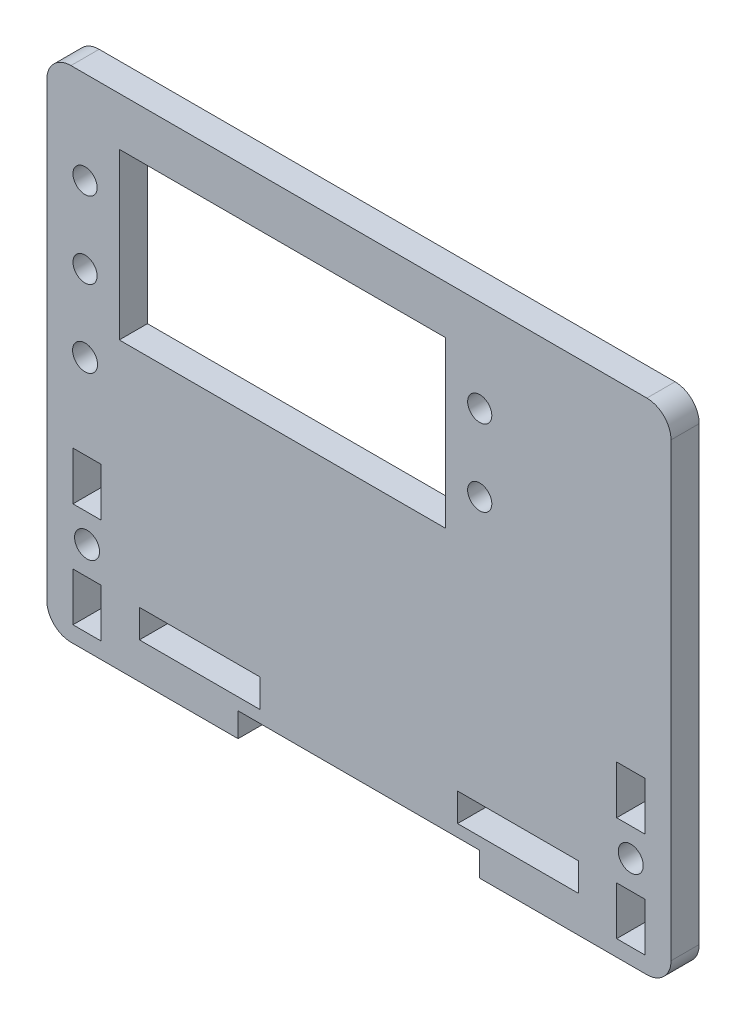
SolidWorks part; units mm, degrees
material "Balsa"
ref_plane "Front Plane" through (0, 0, 0) normal (0, 0, 1) x (1, 0, 0)
ref_plane "Top Plane" through (0, 0, 0) normal (0, 1, 0) x (1, 0, 0)
ref_plane "Right Plane" through (0, 0, 0) normal (1, 0, 0) x (0, 0, -1)
sketch "Sketch1" plane through (0, 0, 0) normal (0, 0, 1) x (1, 0, 0)
  line L1 (-35.75, -31) -> (35.75, -31)
  line L2 (-38.75, -28) -> (-38.75, 28)
  line L3 (-35.75, 31) -> (35.75, 31)
  line L4 (38.75, -28) -> (38.75, 28)
  line L5 (0, 31) -> (0, -31) construction
  line L6 (-38.75, 0) -> (38.75, 0) construction
  line L7 (-29.75, 4.5) -> (10.75, 4.5)
  line L8 (-29.75, 4.5) -> (-29.75, 25)
  line L9 (-29.75, 25) -> (10.75, 25)
  line L10 (10.75, 4.5) -> (10.75, 25)
  arc A0 (35.75, 31) -> (38.75, 28) centre (35.75, 28) cw
  arc A1 (35.75, -31) -> (38.75, -28) centre (35.75, -28) ccw
  arc A2 (-35.75, -31) -> (-38.75, -28) centre (-35.75, -28) cw
  arc A3 (-38.75, 28) -> (-35.75, 31) centre (-35.75, 28) cw
  point P0 (0, 0)
  point P8 (38.75, -31)
  point P12 (-38.75, -31)
  dimension "D2" = 3
  dimension "D3" = 62
  dimension "D1" = 28
  dimension "D4" = 40.5
  dimension "D5" = 20.5
  dimension "D6" = 9
  dimension "D7" = 6
extrude "Boss-Extrude1" add sketch "Sketch1" along normal blind 3.5
sketch "Sketch2" plane through (0, 0, 3.5) normal (0, 0, 1) x (1, 0, 0)
  line L0 (-38.75, -19.5) -> (38.75, -19.5) construction
  line L1 (-35.75, -31) -> (35.75, -31) construction
  line L2 (38.75, -28) -> (38.75, 28) construction
  line L3 (-38.75, 28) -> (-38.75, -28) construction
  line L4 (33.75, -29.922) -> (33.75, 0) construction
  line L5 (32, -16) -> (35.5, -16)
  line L6 (32, -16) -> (32, -10)
  line L7 (32, -10) -> (35.5, -10)
  line L8 (35.5, -16) -> (35.5, -10)
  line L9 (35.5, -23) -> (32, -23)
  line L10 (35.5, -23) -> (35.5, -29)
  line L11 (35.5, -29) -> (32, -29)
  line L12 (32, -23) -> (32, -29)
  line L13 (0, 10.4666) -> (0, -9.03) construction
  line L14 (-35.5, -23) -> (-32, -23)
  line L15 (-32, -23) -> (-32, -29)
  line L16 (-35.5, -29) -> (-32, -29)
  line L17 (-35.5, -23) -> (-35.5, -29)
  line L18 (-32, -16) -> (-35.5, -16)
  line L19 (-32, -16) -> (-32, -10)
  line L20 (-32, -10) -> (-35.5, -10)
  line L21 (-35.5, -16) -> (-35.5, -10)
  circle A1 centre (33.75, -19.5) radius 1.55
  circle A2 centre (-33.75, -19.5) radius 1.55
  dimension "D2" = 0
  dimension "D9" = 3.1
  dimension "D1" = 11.5
  dimension "D3" = 6
  dimension "D4" = 3.5
  dimension "D5" = 6
  dimension "D6" = 19
  dimension "D8" = 5
extrude "Cut-Extrude1" cut sketch "Sketch2" against normal through all
sketch "Sketch3" plane through (0, 0, 3.5) normal (0, 0, 1) x (1, 0, 0)
  line L0 (-32, -23) -> (32, -23) construction
  line L1 (0, 0) -> (0, -31) construction
  line L2 (-27.25, -23) -> (-12.25, -23)
  line L3 (-27.25, -23) -> (-27.25, -26.5)
  line L4 (-27.25, -26.5) -> (-12.25, -26.5)
  line L5 (-12.25, -23) -> (-12.25, -26.5)
  line L6 (-35.75, -31) -> (35.75, -31) construction
  line L8 (27.25, -23) -> (27.25, -26.5)
  line L9 (27.25, -23) -> (12.25, -23)
  line L10 (12.25, -23) -> (12.25, -26.5)
  line L11 (27.25, -26.5) -> (12.25, -26.5)
  dimension "D1" = 24.5
  dimension "D2" = 15
  dimension "D3" = 3.5
extrude "Cut-Extrude2" cut sketch "Sketch3" against normal through all
sketch "Sketch4" plane through (0, 0, 3.5) normal (0, 0, 1) x (1, 0, 0)
  line L0 (-32.7283, 14.75) -> (20.2148, 14.75) construction
  line L1 (10.75, 25) -> (-29.75, 25) construction
  line L2 (-9.5, -1.2649) -> (-9.5, 28.2785) construction
  line L3 (-29.75, 4.5) -> (10.75, 4.5) construction
  line L4 (-29.75, 25) -> (-29.75, 4.5) construction
  line L5 (10.75, 4.5) -> (10.75, 25) construction
  line L7 (-34, 10) -> (15, 10) construction
  line L8 (-34, 10) -> (-34, 19.5) construction
  line L9 (-34, 19.5) -> (15, 19.5) construction
  line L10 (15, 10) -> (15, 19.5) construction
  line L11 (-9.5, 19.5) -> (-9.5, 10) construction
  line L12 (-34, 14.75) -> (15, 14.75) construction
  circle A0 centre (15, 19.5) radius 1.5
  circle A1 centre (15, 10) radius 1.5
  circle A2 centre (-34, 10) radius 1.5
  circle A3 centre (-34, 19.5) radius 1.5
  point P12 (-9.5, 14.75)
  dimension "D3" = 3
  dimension "D1" = 9.5
  dimension "D2" = 49
extrude "Cut-Extrude3" cut sketch "Sketch4" against normal through all both and the other way through all
sketch "Sketch5" plane through (0, 0, 3.5) normal (0, 0, 1) x (1, 0, 0)
  line L0 (-34, 31) -> (-34, -31) construction
  line L3 (35.75, 31) -> (-35.75, 31) construction
  line L6 (-35.75, -31) -> (35.75, -31) construction
  circle A2 centre (-34, 0.5) radius 1.55
  circle A7 centre (-34, 10) radius 1.5 construction
  dimension "D1" = 9.5
extrude "Cut-Extrude4" cut sketch "Sketch5" against normal up to next contours A2
sketch "Sketch6" plane through (0, 0, 3.5) normal (0, 0, 1) x (1, 0, 0)
  line L0 (0, 0) -> (0, -32.3805) construction
  line L1 (-35.75, -31) -> (35.75, -31) construction
  line L2 (-15, -28) -> (15, -28)
  line L3 (-15, -28) -> (-15, -31)
  line L4 (-15, -31) -> (15, -31)
  line L5 (15, -28) -> (15, -31)
  line L6 (-15, -28) -> (15, -31) construction
  line L7 (-15, -31) -> (15, -28) construction
  point P3 (0, -29.5)
  dimension "D1" = 30
  dimension "D2" = 3
extrude "Cut-Extrude5" cut sketch "Sketch6" against normal blind 10
